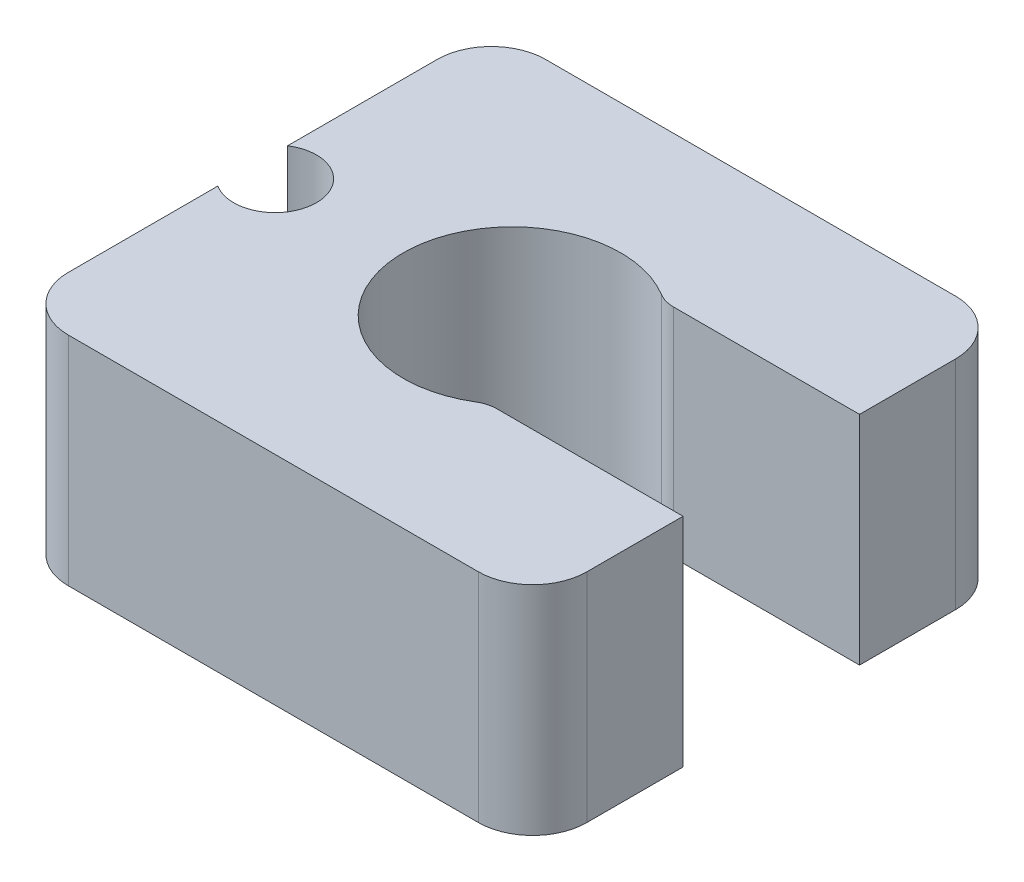
SolidWorks part; units mm, degrees
ref_plane "前基準面" through (0, 0, 0) normal (0, 0, 1) x (1, 0, 0)
ref_plane "上基準面" through (0, 0, 0) normal (0, 1, 0) x (1, 0, 0)
ref_plane "右基準面" through (0, 0, 0) normal (1, 0, 0) x (0, 0, -1)
sketch "草圖4" plane through (0, 0, 0) normal (0, 1, 0) x (1, 0, 0)
  line L1 (-2.3877, 2.1978) -> (2.3877, 2.1978)
  line L2 (-2.3877, 2.1978) -> (-2.3877, -2.1978)
  line L3 (-2.3877, -2.1978) -> (2.3877, -2.1978)
  line L4 (2.3877, 2.1978) -> (2.3877, -2.1978)
  line L5 (-2.3877, 2.1978) -> (2.3877, -2.1978) construction
  line L6 (-2.3877, -2.1978) -> (2.3877, 2.1978) construction
  circle A0 centre (0, 0) radius 1.0019
  circle A1 centre (-2.1819, 0) radius 0.3815
extrude "填料-伸長2" add sketch "草圖4" along normal blind 2 contours A1 L2 L3 L4 L1 A0
sketch "草圖5" plane through (0, 2, 0) normal (0, 1, 0) x (1, 0, 0)
  line L0 (1.0019, 0) -> (2.3877, 0)
  line L1 (2.3877, 2.1978) -> (2.3877, -2.1978) construction
  line L2 (0, 0.5545) -> (0, -0.5545)
  line L3 (0, 0.5545) -> (2.3877, 0.5545)
  line L4 (2.3877, 0.5545) -> (2.3877, -0.5545)
  line L5 (2.3877, -0.5545) -> (0, -0.5545)
  circle A0 centre (0, 0) radius 1.0019 construction
  point P10 (0, 0)
  line M4 (2.3877, -2.1978) -> (2.3877, 2.1978)
  circle M7 centre (0, 0) radius 1.0019
extrude "除料-伸長3" cut sketch "草圖5" against normal blind 2 contours L3 L0 M7 M4 | L5 L0 M4 M7
fillet "圓角1" radius 0.5 1 edges at (2.3877, 1, -2.1978)
fillet "圓角2" radius 0.5 3 edges at (-2.3877, 1, -2.1978) (-2.3877, 1, 2.1978) (2.3877, 1, 2.1978)
fillet "圓角3" radius 0.3 2 edges at (0.8345, 1, 0.5545) (0.8345, 1, -0.5545)
sketch "草圖6" plane through (0, 2, 0) normal (0, 1, 0) x (1, 0, 0)
  line L0 (0, 0) -> (0, -0.8127)
  line L1 (0, -0.8127) -> (2.3877, -0.8127)
  line L2 (2.3877, -0.5545) -> (2.3877, -1.6978) construction
  line L3 (0, 0) -> (0, 0.8127)
  line L4 (0, 0.8127) -> (2.3877, 0.8127)
  line L5 (2.3877, 1.6978) -> (2.3877, 0.5545) construction
  line L6 (2.3877, 0.8127) -> (2.3877, -0.8127)
extrude "除料-伸長4" cut sketch "草圖6" against normal blind 2
fillet "圓角4" radius 0.3 2 edges at (0.5859, 1, -0.8127) (0.5859, 1, 0.8127)
